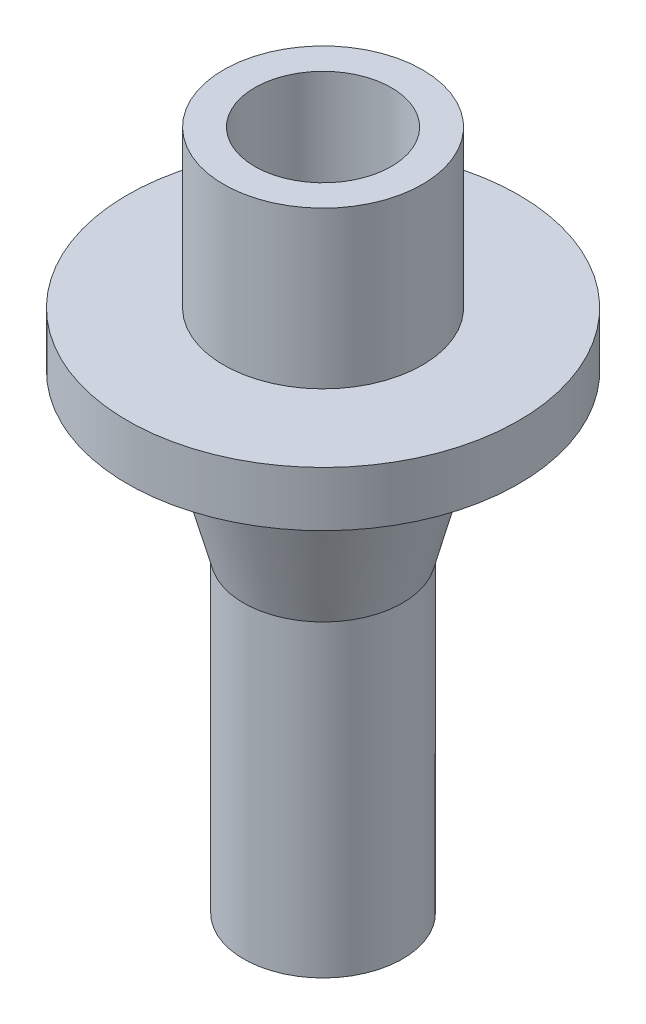
SolidWorks part; units mm, degrees
ref_plane "Front Plane" through (0, 0, 0) normal (0, 0, 1) x (1, 0, 0)
ref_plane "Top Plane" through (0, 0, 0) normal (0, 1, 0) x (1, 0, 0)
ref_plane "Right Plane" through (0, 0, 0) normal (1, 0, 0) x (0, 0, -1)
sketch "Sketch1" plane through (0, 0, 0) normal (1, 0, 0) x (0, 0, -1)
  line L0 (0, 0) -> (0, 97.3762) construction
  line L1 (0, 27) -> (12.7, 27)
  line L2 (12.7, 27) -> (12.7, 7)
  line L3 (12.7, 7) -> (25, 7)
  line L4 (25, 7) -> (25, 0)
  line L5 (25, 0) -> (15.68, 0)
  line L7 (0, 97.3762) -> (0, -129.0791) construction
  line L8 (0, -60) -> (0, 27)
  line L9 (10.16, -60) -> (0, -60)
  line L11 (10.16, 27) -> (10.16, 43.9813) construction
  line L12 (10.16, -60) -> (10.16, -20.6009)
  line L13 (15.68, 0) -> (10.16, -20.6009)
  dimension "D1" = 15
  dimension "D2" = 10.16
  dimension "D3" = 25
  dimension "D4" = 12.7
  dimension "D5" = 7
  dimension "D7" = 20
  dimension "D8" = 60
  dimension "D9" = 15.68
revolve "Revolve1" add sketch "Sketch1" angle 360 about L0
hole_wizard "3/4-16 Tapped Hole1" positions "Sketch3" profile "Sketch4" tap size "3/4-16" standard "ANSI Inch"
sketch "Sketch3" plane through (0, 27, 0) normal (0, 1, 0) x (1, 0, 0)
  point P0 (0, 0)
sketch "Sketch4" plane through (0, 27, 0) normal (1, 0, 0) x (0, 0, 1)
  line L0 (0, 0) -> (0, 25.2463)
  line L1 (0, 25.2463) -> (8.7312, 20)
  line L2 (8.7312, 20) -> (8.7312, 0)
  line L5 (8.7312, 0) -> (0, 0)
  line L10 (0, 25.2463) -> (-8.7313, 20) construction
  line L11 (0, -6.35) -> (0, 107.95) construction
  dimension "Tap Drill Dia." = 17.4625
  dimension "Tap Drill Depth" = 20
  dimension "Drill Angle" = 118
cosmetic thread "Hole Thread1" parameters "D1"=38.1, "D2"=19.05
sketch "Sketch5" plane through (0, -60, 0) normal (0, -1, 0) x (1, 0, 0)
  circle A1 centre (0, 0) radius 7.5
  dimension "D1" = 15
extrude "Cut-Extrude1" cut sketch "Sketch5" against normal up to next
